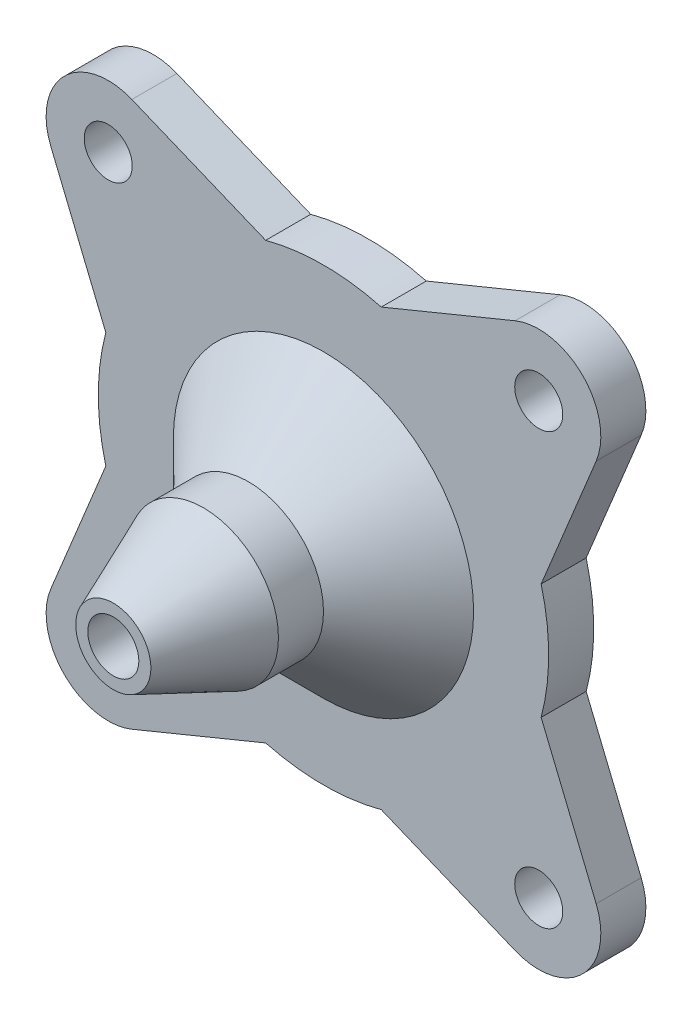
SolidWorks part; units mm, degrees
ref_plane "Front Plane" through (0, 0, 0) normal (0, 0, 1) x (1, 0, 0)
ref_plane "Top Plane" through (0, 0, 0) normal (0, 1, 0) x (1, 0, 0)
ref_plane "Right Plane" through (0, 0, 0) normal (1, 0, 0) x (0, 0, -1)
sketch "Sketch1" plane through (0, 0, 0) normal (0, 0, 1) x (1, 0, 0)
  circle A0 centre (0, 0) radius 15
  dimension "D1" = 30
extrude "Boss-Extrude1" add sketch "Sketch1" along normal blind 3
sketch "Sketch2" plane through (0, 0, 3) normal (0, 0, 1) x (1, 0, 0)
  line L0 (-18.1636, 12.7645) -> (-14.4977, 3.8492)
  line L1 (-12.7645, 18.1636) -> (-3.8492, 14.4977)
  line L2 (0, 0) -> (-13.4281, 13.4281) construction
  line L3 (0, 0) -> (-10.9925, 0) construction
  circle A0 centre (-14.3377, 14.3377) radius 1.6
  arc A1 (-12.7645, 18.1636) -> (-18.1636, 12.7645) centre (-14.3377, 14.3377) ccw
  circle A2 centre (0, 0) radius 15 construction
  arc A4 (-3.8492, 14.4977) -> (-14.4977, 3.8492) centre (0, 0) ccw
  dimension "D1" = 3.2
  dimension "D2" = 45
extrude "Boss-Extrude2" add sketch "Sketch2" along normal mid plane 3 from offset 1.5 offset against normal yes
mirror "Mirror1" about plane through (0, 0, 0) normal (1, 0, 0) of "Boss-Extrude2"
mirror "Mirror2" about plane through (0, 0, 0) normal (0, 1, 0) of "Boss-Extrude2", "Mirror1"
sketch "Sketch3" plane through (0, 0, 3) normal (0, 0, 1) x (1, 0, 0)
  circle A0 centre (0, 0) radius 5
  dimension "D1" = 10
extrude "Boss-Extrude3" add sketch "Sketch3" along normal blind 8
sketch "Sketch4" plane through (0, 0, 0) normal (0, 1, 0) x (1, 0, 0)
  line L0 (0, -11) -> (0, -17) construction
  line L1 (-5, -11) -> (5, -11) construction
  line L2 (0, -11) -> (-5, -11)
  line L3 (0, -17) -> (-2.5, -17)
  line L4 (-5, -11) -> (-2.5, -17)
  line L5 (0, -11) -> (0, -17)
  dimension "D1" = 5
  dimension "D2" = 2.5
  dimension "D3" = 6
revolve "Revolve1" add sketch "Sketch4" angle 360 about L0
sketch "Sketch5" plane through (0, 0, 17) normal (0, 0, 1) x (1, 0, 0)
  circle A0 centre (0, 0) radius 1.7
  dimension "D1" = 3.4
chamfer "Chamfer1" distance 5 angle 45 1 edges at (5, 0, 3)
extrude "Cut-Extrude1" cut sketch "Sketch5" against normal blind 12
